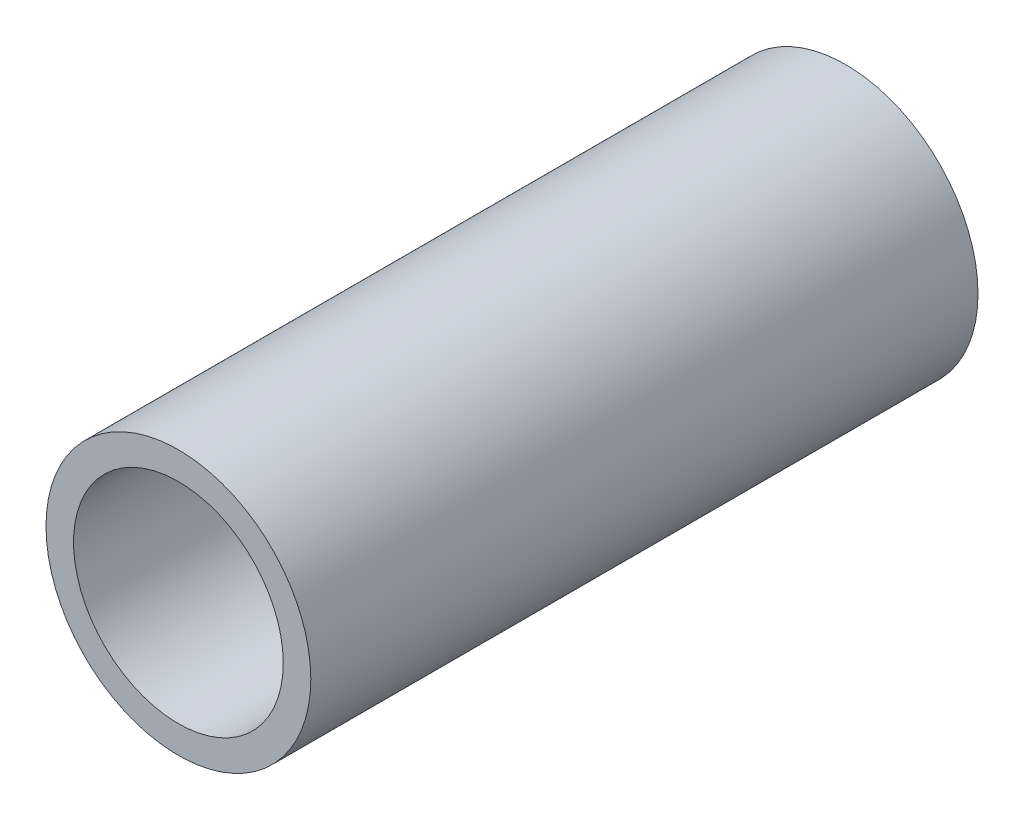
SolidWorks part; units mm, degrees
material "AISI 1020"
ref_plane "Front Plane" through (0, 0, 0) normal (0, 0, 1) x (1, 0, 0)
ref_plane "Top Plane" through (0, 0, 0) normal (0, 1, 0) x (1, 0, 0)
ref_plane "Right Plane" through (0, 0, 0) normal (1, 0, 0) x (0, 0, -1)
sketch "Sketch1" plane through (0, 0, 0) normal (0, 0, 1) x (1, 0, 0)
  circle A0 centre (0, 0) radius 7.9375
  circle A1 centre (0, 0) radius 6.2865
  dimension "D1" = 15.875
  dimension "D2" = 1.651
extrude "Boss-Extrude1" add sketch "Sketch1" along normal blind 40
